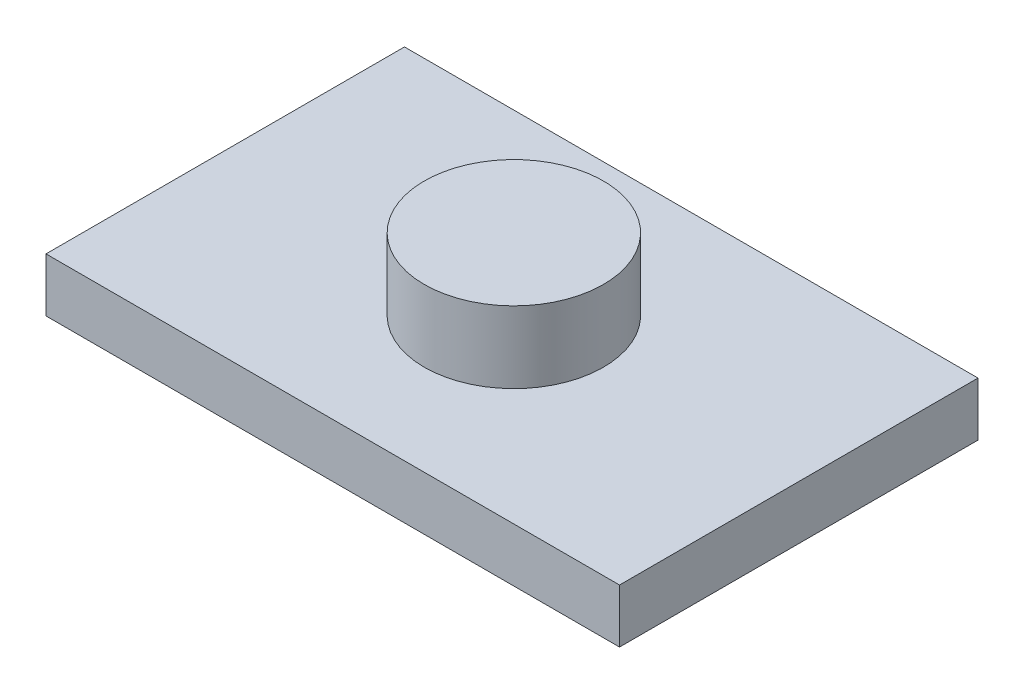
SolidWorks part; units mm, degrees
material "AISI 1020"
ref_plane "Front Plane" through (0, 0, 0) normal (0, 0, 1) x (1, 0, 0)
ref_plane "Top Plane" through (0, 0, 0) normal (0, 1, 0) x (1, 0, 0)
ref_plane "Right Plane" through (0, 0, 0) normal (1, 0, 0) x (0, 0, -1)
sketch "Sketch1" plane through (0, 0, 0) normal (0, 1, 0) x (1, 0, 0)
  line L1 (1794.8706, 929.4118) -> (1896.4706, 929.4118)
  line L2 (1794.8706, 929.4118) -> (1794.8706, 865.9118)
  line L3 (1794.8706, 865.9118) -> (1896.4706, 865.9118)
  line L4 (1896.4706, 929.4118) -> (1896.4706, 865.9118)
  line L5 (1794.8706, 929.4118) -> (1896.4706, 865.9118) construction
  line L6 (1794.8706, 865.9118) -> (1896.4706, 929.4118) construction
  point P0 (1845.6706, 897.6618)
  dimension "D1" = 101.6
  dimension "D2" = 63.5
extrude "Plate" add sketch "Sketch1" along normal blind 9.525 contours L1 L4 L3 L2
sketch "Sketch2" plane through (0, 9.525, 0) normal (0, 1, 0) x (1, 0, 0)
  circle A0 centre (1845.7651, 897.898) radius 15.875
  point P2 (0, 0)
  dimension "D1" = 31.75
extrude "Boss" add sketch "Sketch2" along normal blind 12.7
